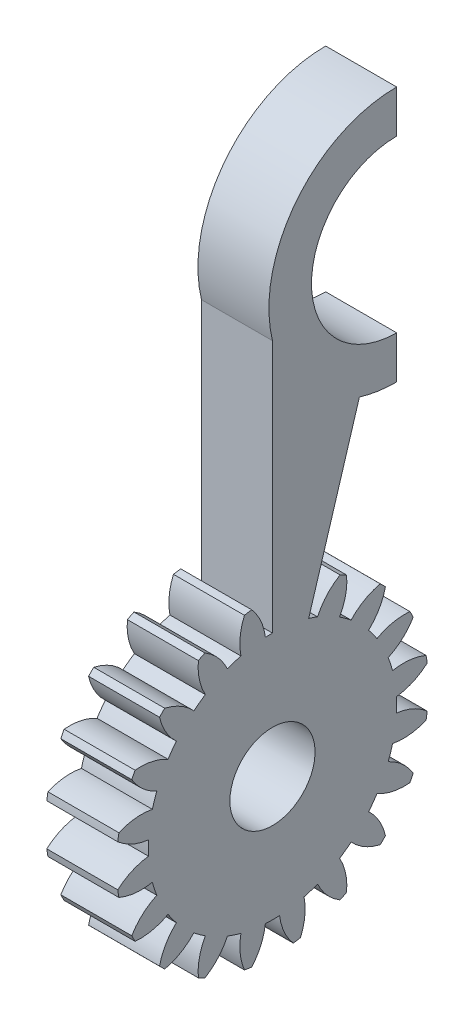
SolidWorks part; units mm, degrees
ref_plane "正面" through (0, 0, 0) normal (0, 0, 1) x (1, 0, 0)
ref_plane "平面" through (0, 0, 0) normal (0, 1, 0) x (1, 0, 0)
ref_plane "右側面" through (0, 0, 0) normal (1, 0, 0) x (0, 0, -1)
ref_plane "平面1" through (-4.1584, 0, 0) normal (1, 0, 0) x (0, 0, -1)
sketch "ｽｹｯﾁ1" plane through (-4.1584, 0, 0) normal (1, 0, 0) x (0, 0, -1)
  circle A0 centre (0, 2.9825) radius 3
  arc A1 (-10.902, 4.4474) -> (-8.7347, 3.4824) centre (-8.2645, 7.4547) ccw
  arc A2 (-8.7347, 3.4824) -> (-8.7347, 2.4826) centre (0, 2.9825) ccw
  arc A3 (-8.7347, 2.4826) -> (-10.902, 1.5175) centre (-8.2645, -1.4897) ccw
  arc A4 (-10.902, 1.5175) -> (-10.8211, 1.0068) centre (0, 2.9825) ccw
  arc A5 (-10.8211, 1.0068) -> (-8.4617, 0.7588) centre (-9.242, 4.6819) ccw
  arc A6 (-8.4617, 0.7588) -> (-8.1527, -0.1921) centre (0, 2.9825) ccw
  arc A7 (-8.1527, -0.1921) -> (-9.9157, -1.7797) centre (-6.478, -3.8247) ccw
  arc A8 (-9.9157, -1.7797) -> (-9.681, -2.2404) centre (0, 2.9825) ccw
  arc A9 (-9.681, -2.2404) -> (-7.3604, -1.7472) centre (-9.3148, 1.7428) ccw
  arc A10 (-7.3604, -1.7472) -> (-6.7727, -2.5561) centre (0, 2.9825) ccw
  arc A11 (-6.7727, -2.5561) -> (-7.9588, -4.6107) centre (-4.0574, -5.4933) ccw
  arc A12 (-7.9588, -4.6107) -> (-7.5932, -4.9764) centre (0, 2.9825) ccw
  arc A13 (-7.5932, -4.9764) -> (-5.5386, -3.7902) centre (-8.4758, -1.0749) ccw
  arc A14 (-5.5386, -3.7902) -> (-4.7297, -4.3779) centre (0, 2.9825) ccw
  arc A15 (-4.7297, -4.3779) -> (-5.2229, -6.6985) centre (-1.2397, -6.3323) ccw
  arc A16 (-5.2229, -6.6985) -> (-4.7622, -6.9333) centre (0, 2.9825) ccw
  arc A17 (-4.7622, -6.9333) -> (-3.1746, -5.1702) centre (-6.8072, -3.4955) ccw
  arc A18 (-3.1746, -5.1702) -> (-2.2237, -5.4792) centre (0, 2.9825) ccw
  arc A19 (-2.2237, -5.4792) -> (-1.9757, -7.8386) centre (1.6994, -6.2595) ccw
  arc A20 (-1.9757, -7.8386) -> (-1.465, -7.9195) centre (0, 2.9825) ccw
  arc A21 (-1.465, -7.9195) -> (-0.4999, -5.7522) centre (-4.4722, -5.282) ccw
  arc A22 (-0.4999, -5.7522) -> (0.4999, -5.7522) centre (0, 2.9825) ccw
  arc A23 (0.4999, -5.7522) -> (1.465, -7.9195) centre (4.4722, -5.282) ccw
  arc A24 (1.465, -7.9195) -> (1.9757, -7.8386) centre (0, 2.9825) ccw
  arc A25 (1.9757, -7.8386) -> (2.2237, -5.4792) centre (-1.6994, -6.2595) ccw
  arc A26 (2.2237, -5.4792) -> (3.1746, -5.1702) centre (0, 2.9825) ccw
  arc A27 (3.1746, -5.1702) -> (4.7622, -6.9333) centre (6.8072, -3.4955) ccw
  arc A28 (4.7622, -6.9333) -> (5.2229, -6.6985) centre (0, 2.9825) ccw
  arc A29 (5.2229, -6.6985) -> (4.7297, -4.3779) centre (1.2397, -6.3323) ccw
  arc A30 (4.7297, -4.3779) -> (5.5386, -3.7902) centre (0, 2.9825) ccw
  arc A31 (5.5386, -3.7902) -> (7.5932, -4.9764) centre (8.4758, -1.0749) ccw
  arc A32 (7.5932, -4.9764) -> (7.9588, -4.6107) centre (0, 2.9825) ccw
  arc A33 (7.9588, -4.6107) -> (6.7727, -2.5561) centre (4.0574, -5.4933) ccw
  arc A34 (6.7727, -2.5561) -> (7.3604, -1.7472) centre (0, 2.9825) ccw
  arc A35 (7.3604, -1.7472) -> (9.681, -2.2404) centre (9.3148, 1.7428) ccw
  arc A36 (9.681, -2.2404) -> (9.9157, -1.7797) centre (0, 2.9825) ccw
  arc A37 (9.9157, -1.7797) -> (8.1527, -0.1921) centre (6.478, -3.8247) ccw
  arc A38 (8.1527, -0.1921) -> (8.4617, 0.7588) centre (0, 2.9825) ccw
  arc A39 (8.4617, 0.7588) -> (10.8211, 1.0068) centre (9.242, 4.6819) ccw
  arc A40 (10.8211, 1.0068) -> (10.902, 1.5175) centre (0, 2.9825) ccw
  arc A41 (10.902, 1.5175) -> (8.7347, 2.4826) centre (8.2645, -1.4897) ccw
  arc A42 (8.7347, 2.4826) -> (8.7347, 3.4824) centre (0, 2.9825) ccw
  arc A43 (8.7347, 3.4824) -> (10.902, 4.4474) centre (8.2645, 7.4547) ccw
  arc A44 (10.902, 4.4474) -> (10.8211, 4.9581) centre (0, 2.9825) ccw
  arc A45 (10.8211, 4.9581) -> (8.4617, 5.2062) centre (9.242, 1.283) ccw
  arc A46 (8.4617, 5.2062) -> (8.1527, 6.1571) centre (0, 2.9825) ccw
  arc A47 (8.1527, 6.1571) -> (9.9157, 7.7446) centre (6.478, 9.7897) ccw
  arc A48 (9.9157, 7.7446) -> (9.681, 8.2053) centre (0, 2.9825) ccw
  arc A49 (9.681, 8.2053) -> (7.3604, 7.7122) centre (9.3148, 4.2221) ccw
  arc A50 (7.3604, 7.7122) -> (6.7727, 8.5211) centre (0, 2.9825) ccw
  arc A51 (6.7727, 8.5211) -> (7.9588, 10.5757) centre (4.0574, 11.4583) ccw
  arc A52 (7.9588, 10.5757) -> (7.5932, 10.9413) centre (0, 2.9825) ccw
  arc A53 (7.5932, 10.9413) -> (5.5386, 9.7552) centre (8.4758, 7.0399) ccw
  arc A54 (5.5386, 9.7552) -> (4.7297, 10.3429) centre (0, 2.9825) ccw
  arc A55 (4.7297, 10.3429) -> (5.2229, 12.6635) centre (1.2397, 12.2973) ccw
  arc A56 (5.2229, 12.6635) -> (4.7622, 12.8982) centre (0, 2.9825) ccw
  arc A57 (4.7622, 12.8982) -> (3.1746, 11.1352) centre (6.8072, 9.4605) ccw
  arc A58 (3.1746, 11.1352) -> (2.2237, 11.4442) centre (0, 2.9825) ccw
  arc A59 (2.2237, 11.4442) -> (1.9757, 13.8036) centre (-1.6994, 12.2245) ccw
  arc A60 (1.9757, 13.8036) -> (1.465, 13.8845) centre (0, 2.9825) ccw
  arc A61 (1.465, 13.8845) -> (0.4999, 11.7172) centre (4.4722, 11.247) ccw
  arc A62 (0.4999, 11.7172) -> (-0.4999, 11.7172) centre (0, 2.9825) ccw
  arc A63 (-0.4999, 11.7172) -> (-1.465, 13.8845) centre (-4.4722, 11.247) ccw
  arc A64 (-1.465, 13.8845) -> (-1.9757, 13.8036) centre (0, 2.9825) ccw
  arc A65 (-1.9757, 13.8036) -> (-2.2237, 11.4442) centre (1.6994, 12.2245) ccw
  arc A66 (-2.2237, 11.4442) -> (-3.1746, 11.1352) centre (0, 2.9825) ccw
  arc A67 (-3.1746, 11.1352) -> (-4.7622, 12.8982) centre (-6.8072, 9.4605) ccw
  arc A68 (-4.7622, 12.8982) -> (-5.2229, 12.6635) centre (0, 2.9825) ccw
  arc A69 (-5.2229, 12.6635) -> (-4.7297, 10.3429) centre (-1.2397, 12.2973) ccw
  arc A70 (-4.7297, 10.3429) -> (-5.5386, 9.7552) centre (0, 2.9825) ccw
  arc A71 (-5.5386, 9.7552) -> (-7.5932, 10.9413) centre (-8.4758, 7.0399) ccw
  arc A72 (-7.5932, 10.9413) -> (-7.9588, 10.5757) centre (0, 2.9825) ccw
  arc A73 (-7.9588, 10.5757) -> (-6.7727, 8.5211) centre (-4.0574, 11.4583) ccw
  arc A74 (-6.7727, 8.5211) -> (-7.3604, 7.7122) centre (0, 2.9825) ccw
  arc A75 (-7.3604, 7.7122) -> (-9.681, 8.2053) centre (-9.3148, 4.2221) ccw
  arc A76 (-9.681, 8.2053) -> (-9.9157, 7.7446) centre (0, 2.9825) ccw
  arc A77 (-9.9157, 7.7446) -> (-8.1527, 6.1571) centre (-6.478, 9.7897) ccw
  arc A78 (-8.1527, 6.1571) -> (-8.4617, 5.2062) centre (0, 2.9825) ccw
  arc A79 (-8.4617, 5.2062) -> (-10.8211, 4.9581) centre (-9.242, 1.283) ccw
  arc A80 (-10.8211, 4.9581) -> (-10.902, 4.4474) centre (0, 2.9825) ccw
sketch "ｽｹｯﾁ2" plane through (-4.1584, 0, 0) normal (1, 0, 0) x (0, 0, -1)
  line L0 (0, 2.9825) -> (8.749, 31.6784) construction
  line L1 (8.749, 31.6784) -> (8.749, 2.9825) construction
  line L2 (8.749, 2.9825) -> (0, 2.9825) construction
  line L3 (0, 2.9825) -> (0, 34.3458) construction
  line L4 (8.749, 22.6784) -> (8.749, 25.6784)
  line L5 (8.749, 37.6784) -> (8.749, 40.6784)
  line L6 (0, 11.7315) -> (0, 29.5677)
  line L7 (2.5515, 11.3512) -> (6.1243, 23.0696)
  arc A0 (8.7347, 2.4826) -> (8.7347, 3.4824) centre (0, 2.9825) ccw construction
  arc A1 (8.749, 37.6784) -> (8.749, 25.6784) centre (8.749, 31.6784) ccw
  arc A2 (8.749, 40.6784) -> (0, 29.5677) centre (8.749, 31.6784) ccw
  arc A3 (6.1243, 23.0696) -> (8.749, 22.6784) centre (8.749, 31.6784) ccw
  circle A4 centre (8.749, 31.6784) radius 9 construction
  circle A5 centre (8.749, 31.6784) radius 6 construction
  circle A6 centre (0, 2.9825) radius 3
  arc A7 (-10.902, 4.4474) -> (-8.7347, 3.4824) centre (-8.2645, 7.4547) ccw
  arc A8 (-8.7347, 3.4824) -> (-8.7347, 2.4826) centre (0, 2.9825) ccw
  arc A9 (-8.7347, 2.4826) -> (-10.902, 1.5175) centre (-8.2645, -1.4897) ccw
  arc A10 (-10.902, 1.5175) -> (-10.8211, 1.0068) centre (0, 2.9825) ccw
  arc A11 (-10.8211, 1.0068) -> (-8.4617, 0.7588) centre (-9.242, 4.6819) ccw
  arc A12 (-8.4617, 0.7588) -> (-8.1527, -0.1921) centre (0, 2.9825) ccw
  arc A13 (-8.1527, -0.1921) -> (-9.9157, -1.7797) centre (-6.478, -3.8247) ccw
  arc A14 (-9.9157, -1.7797) -> (-9.681, -2.2404) centre (0, 2.9825) ccw
  arc A15 (-9.681, -2.2404) -> (-7.3604, -1.7472) centre (-9.3148, 1.7428) ccw
  arc A16 (-7.3604, -1.7472) -> (-6.7727, -2.5561) centre (0, 2.9825) ccw
  arc A17 (-6.7727, -2.5561) -> (-7.9588, -4.6107) centre (-4.0574, -5.4933) ccw
  arc A18 (-7.9588, -4.6107) -> (-7.5932, -4.9764) centre (0, 2.9825) ccw
  arc A19 (-7.5932, -4.9764) -> (-5.5386, -3.7902) centre (-8.4758, -1.0749) ccw
  arc A20 (-5.5386, -3.7902) -> (-4.7297, -4.3779) centre (0, 2.9825) ccw
  arc A21 (-4.7297, -4.3779) -> (-5.2229, -6.6985) centre (-1.2397, -6.3323) ccw
  arc A22 (-5.2229, -6.6985) -> (-4.7622, -6.9333) centre (0, 2.9825) ccw
  arc A23 (-4.7622, -6.9333) -> (-3.1746, -5.1702) centre (-6.8072, -3.4955) ccw
  arc A24 (-3.1746, -5.1702) -> (-2.2237, -5.4792) centre (0, 2.9825) ccw
  arc A25 (-2.2237, -5.4792) -> (-1.9757, -7.8386) centre (1.6994, -6.2595) ccw
  arc A26 (-1.9757, -7.8386) -> (-1.465, -7.9195) centre (0, 2.9825) ccw
  arc A27 (-1.465, -7.9195) -> (-0.4999, -5.7522) centre (-4.4722, -5.282) ccw
  arc A28 (-0.4999, -5.7522) -> (0.4999, -5.7522) centre (0, 2.9825) ccw
  arc A29 (0.4999, -5.7522) -> (1.465, -7.9195) centre (4.4722, -5.282) ccw
  arc A30 (1.465, -7.9195) -> (1.9757, -7.8386) centre (0, 2.9825) ccw
  arc A31 (1.9757, -7.8386) -> (2.2237, -5.4792) centre (-1.6994, -6.2595) ccw
  arc A32 (2.2237, -5.4792) -> (3.1746, -5.1702) centre (0, 2.9825) ccw
  arc A33 (3.1746, -5.1702) -> (4.7622, -6.9333) centre (6.8072, -3.4955) ccw
  arc A34 (4.7622, -6.9333) -> (5.2229, -6.6985) centre (0, 2.9825) ccw
  arc A35 (5.2229, -6.6985) -> (4.7297, -4.3779) centre (1.2397, -6.3323) ccw
  arc A36 (4.7297, -4.3779) -> (5.5386, -3.7902) centre (0, 2.9825) ccw
  arc A37 (5.5386, -3.7902) -> (7.5932, -4.9764) centre (8.4758, -1.0749) ccw
  arc A38 (7.5932, -4.9764) -> (7.9588, -4.6107) centre (0, 2.9825) ccw
  arc A39 (7.9588, -4.6107) -> (6.7727, -2.5561) centre (4.0574, -5.4933) ccw
  arc A40 (6.7727, -2.5561) -> (7.3604, -1.7472) centre (0, 2.9825) ccw
  arc A41 (7.3604, -1.7472) -> (9.681, -2.2404) centre (9.3148, 1.7428) ccw
  arc A42 (9.681, -2.2404) -> (9.9157, -1.7797) centre (0, 2.9825) ccw
  arc A43 (9.9157, -1.7797) -> (8.1527, -0.1921) centre (6.478, -3.8247) ccw
  arc A44 (8.1527, -0.1921) -> (8.4617, 0.7588) centre (0, 2.9825) ccw
  arc A45 (8.4617, 0.7588) -> (10.8211, 1.0068) centre (9.242, 4.6819) ccw
  arc A46 (10.8211, 1.0068) -> (10.902, 1.5175) centre (0, 2.9825) ccw
  arc A47 (10.902, 1.5175) -> (8.7347, 2.4826) centre (8.2645, -1.4897) ccw
  arc A48 (8.7347, 2.4826) -> (8.7347, 3.4824) centre (0, 2.9825) ccw
  arc A49 (8.7347, 3.4824) -> (10.902, 4.4474) centre (8.2645, 7.4547) ccw
  arc A50 (10.902, 4.4474) -> (10.8211, 4.9581) centre (0, 2.9825) ccw
  arc A51 (10.8211, 4.9581) -> (8.4617, 5.2062) centre (9.242, 1.283) ccw
  arc A52 (8.4617, 5.2062) -> (8.1527, 6.1571) centre (0, 2.9825) ccw
  arc A53 (8.1527, 6.1571) -> (9.9157, 7.7446) centre (6.478, 9.7897) ccw
  arc A54 (9.9157, 7.7446) -> (9.681, 8.2053) centre (0, 2.9825) ccw
  arc A55 (9.681, 8.2053) -> (7.3604, 7.7122) centre (9.3148, 4.2221) ccw
  arc A56 (7.3604, 7.7122) -> (6.7727, 8.5211) centre (0, 2.9825) ccw
  arc A57 (6.7727, 8.5211) -> (7.9588, 10.5757) centre (4.0574, 11.4583) ccw
  arc A58 (7.9588, 10.5757) -> (7.5932, 10.9413) centre (0, 2.9825) ccw
  arc A59 (7.5932, 10.9413) -> (5.5386, 9.7552) centre (8.4758, 7.0399) ccw
  arc A60 (5.5386, 9.7552) -> (4.7297, 10.3429) centre (0, 2.9825) ccw
  arc A61 (4.7297, 10.3429) -> (5.2229, 12.6635) centre (1.2397, 12.2973) ccw
  arc A62 (5.2229, 12.6635) -> (4.7622, 12.8982) centre (0, 2.9825) ccw
  arc A63 (4.7622, 12.8982) -> (3.1746, 11.1352) centre (6.8072, 9.4605) ccw
  arc A64 (3.1746, 11.1352) -> (2.5515, 11.3512) centre (0, 2.9825) ccw
  arc A68 (0, 11.7315) -> (-0.4999, 11.7172) centre (0, 2.9825) ccw
  arc A69 (-0.4999, 11.7172) -> (-1.465, 13.8845) centre (-4.4722, 11.247) ccw
  arc A70 (-1.465, 13.8845) -> (-1.9757, 13.8036) centre (0, 2.9825) ccw
  arc A71 (-1.9757, 13.8036) -> (-2.2237, 11.4442) centre (1.6994, 12.2245) ccw
  arc A72 (-2.2237, 11.4442) -> (-3.1746, 11.1352) centre (0, 2.9825) ccw
  arc A73 (-3.1746, 11.1352) -> (-4.7622, 12.8982) centre (-6.8072, 9.4605) ccw
  arc A74 (-4.7622, 12.8982) -> (-5.2229, 12.6635) centre (0, 2.9825) ccw
  arc A75 (-5.2229, 12.6635) -> (-4.7297, 10.3429) centre (-1.2397, 12.2973) ccw
  arc A76 (-4.7297, 10.3429) -> (-5.5386, 9.7552) centre (0, 2.9825) ccw
  arc A77 (-5.5386, 9.7552) -> (-7.5932, 10.9413) centre (-8.4758, 7.0399) ccw
  arc A78 (-7.5932, 10.9413) -> (-7.9588, 10.5757) centre (0, 2.9825) ccw
  arc A79 (-7.9588, 10.5757) -> (-6.7727, 8.5211) centre (-4.0574, 11.4583) ccw
  arc A80 (-6.7727, 8.5211) -> (-7.3604, 7.7122) centre (0, 2.9825) ccw
  arc A81 (-7.3604, 7.7122) -> (-9.681, 8.2053) centre (-9.3148, 4.2221) ccw
  arc A82 (-9.681, 8.2053) -> (-9.9157, 7.7446) centre (0, 2.9825) ccw
  arc A83 (-9.9157, 7.7446) -> (-8.1527, 6.1571) centre (-6.478, 9.7897) ccw
  arc A84 (-8.1527, 6.1571) -> (-8.4617, 5.2062) centre (0, 2.9825) ccw
  arc A85 (-8.4617, 5.2062) -> (-10.8211, 4.9581) centre (-9.242, 1.283) ccw
  arc A86 (-10.8211, 4.9581) -> (-10.902, 4.4474) centre (0, 2.9825) ccw
  point P12 (14.4868, 33.4326)
  point P14 (17.749, 31.6784)
  dimension "D2" = 12
  dimension "D1" = 30
  dimension "D3" = 3
extrude "ﾎﾞｽ - 押し出し2" add sketch "ｽｹｯﾁ2" along normal blind 5
